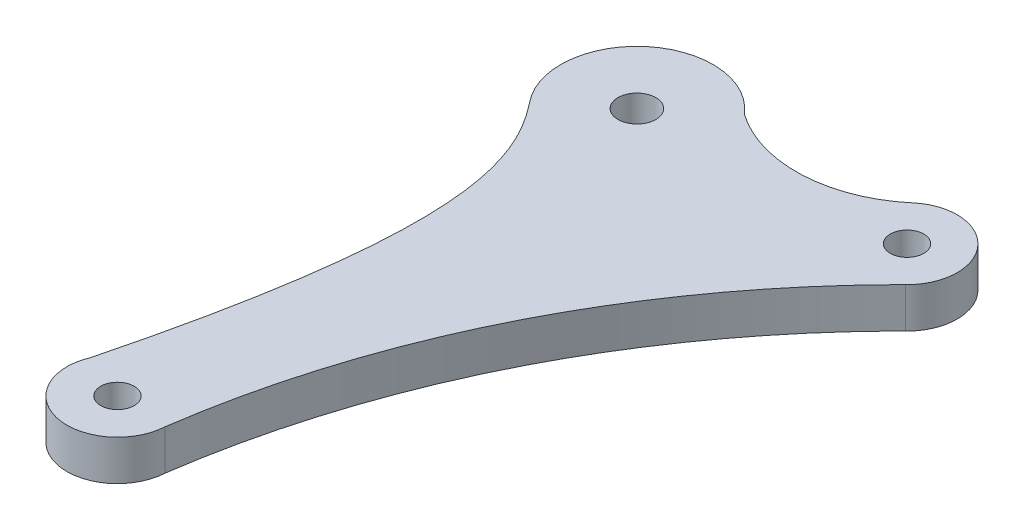
SolidWorks part; units mm, degrees
ref_plane "Front Plane" through (0, 0, 0) normal (0, 0, 1) x (1, 0, 0)
ref_plane "Top Plane" through (0, 0, 0) normal (0, 1, 0) x (1, 0, 0)
ref_plane "Right Plane" through (0, 0, 0) normal (1, 0, 0) x (0, 0, -1)
sketch "Sketch1" plane through (0, 0, 0) normal (0, 1, 0) x (1, 0, 0)
  line L0 (-9.7501, 16.9589) -> (-0.5145, 24.6744) construction
  circle A0 centre (-5.989, -19.3305) radius 1.3244
  arc A1 (-9.6659, -17.7713) -> (-2.002, -19.5626) centre (-5.989, -19.3305) ccw
  circle A2 centre (14.7676, 22.2386) radius 1.3242
  arc A3 (17.5135, 19.3834) -> (12.2026, 25.2575) centre (14.7676, 22.2386) ccw
  circle A4 centre (-5.1323, 20.8166) radius 1.4976
  arc A5 (-0.5145, 24.6744) -> (-9.7501, 16.9589) centre (-5.1323, 20.8166) ccw
  arc A6 (12.2026, 25.2575) -> (-0.5145, 24.6744) centre (5.4672, 33.1845) cw
  spline S14 degree 3 poles (-9.6659, -17.7713) (-3.5832, 6.0102) (-6.3847, 12.6734) (-9.7501, 16.9589) knots 4 4 4 4 5 5 5 5
  spline S21 degree 3 poles (17.5135, 19.3834) (6.9467, 8.8751) (0.0966, -4.7955) (-2.002, -19.5626) knots 13 13 13 13 14 14 14 14
extrude "Boss-Extrude1" add sketch "Sketch1" along normal blind 3.175
